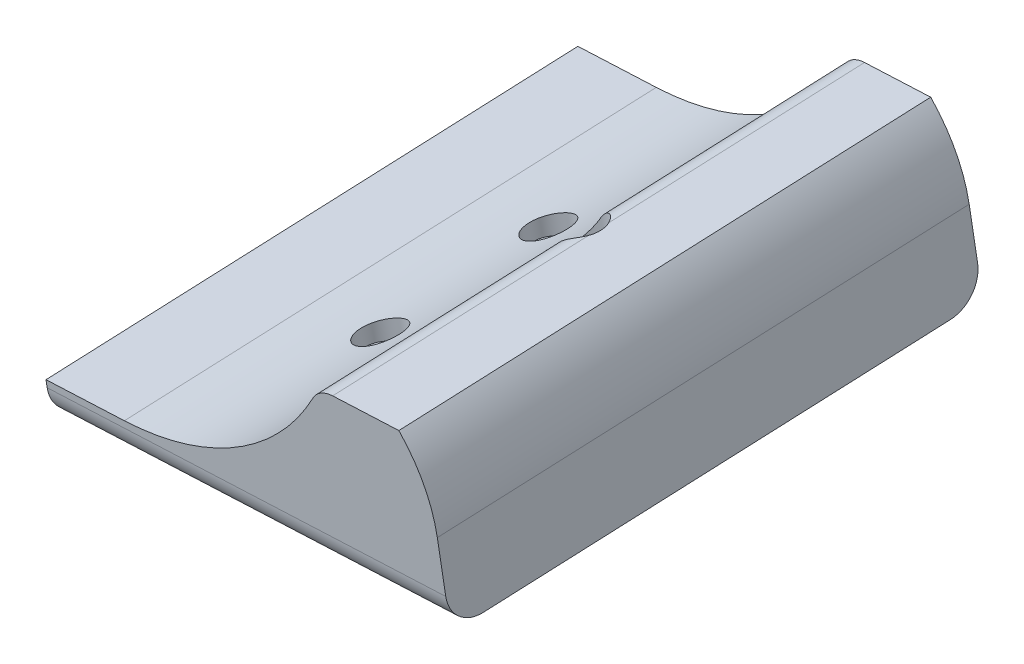
SolidWorks part; units mm, degrees
material "ABS"
ref_plane "Front Plane" through (0, 0, 0) normal (0, 0, 1) x (1, 0, 0)
ref_plane "Top Plane" through (0, 0, 0) normal (0, 1, 0) x (1, 0, 0)
ref_plane "Right Plane" through (0, 0, 0) normal (1, 0, 0) x (0, 0, -1)
other "Configuration Table"
sketch "草图1" plane through (-39.5961, -89.3101, 1121.4165) normal (0.0352, 0.0793, -0.9962) x (-0.9994, 0.0028, -0.0351)
  line L0 (-262.0756, 359.156) -> (-261.6287, 364.136) construction
  line L1 (-262.0756, 359.156) -> (-321.8355, 364.5185) construction
  line L2 (-321.3886, 369.4985) -> (-321.8355, 364.5185) construction
  line L3 (-262.0756, 359.156) -> (-261.6287, 364.136)
  line L4 (-262.0756, 359.156) -> (-321.8355, 364.5185)
  line L5 (-320.7344, 376.7892) -> (-321.3886, 369.4985)
  line L6 (-321.3886, 369.4985) -> (-261.6287, 364.136)
  line L7 (-261.6287, 364.136) -> (-261.4359, 366.2849)
  line L8 (-260.4634, 369.7758) -> (-248.7767, 393.7308)
  line L9 (-287.343, 419.7795) -> (-315.6618, 388.4015)
  line L10 (-320.7344, 376.7892) -> (-321.3886, 369.4985)
  line L12 (-261.6287, 364.136) -> (-261.4359, 366.2849)
  line L13 (-260.4634, 369.7758) -> (-248.7767, 393.7308)
  line L14 (-287.343, 419.7795) -> (-315.6618, 388.4015)
  line L15 (-321.3886, 369.4985) -> (-321.8355, 364.5185)
  arc A3 (-260.4634, 369.7758) -> (-261.4359, 366.2849) centre (-251.4759, 365.3912) ccw
  arc A4 (-248.7767, 393.7308) -> (-287.343, 419.7795) centre (-269.8973, 404.0347) ccw
  arc A5 (-315.6618, 388.4015) -> (-320.7344, 376.7892) centre (-300.8144, 375.0017) ccw
  arc A6 (-260.4634, 369.7758) -> (-261.4359, 366.2849) centre (-251.4759, 365.3912) ccw
  arc A7 (-248.7767, 393.7308) -> (-287.343, 419.7795) centre (-269.8973, 404.0347) ccw
  arc A8 (-315.6618, 388.4015) -> (-320.7344, 376.7892) centre (-300.8144, 375.0017) ccw
  dimension "D1" = 0
extrude "凸台-拉伸1" add sketch "草图1" along normal up to surface (75 mm away)
sketch "草图2" plane through (351.4955, 30.4789, 14.8383) normal (0.9954, 0.0863, 0.042) x (0.0419, 0.0036, -0.9991)
  line L0 (-1074.8827, 277.7422) -> (-1077.4503, 311.4279) construction
  line L1 (-1074.8827, 277.7422) -> (-1073.9691, 265.7578) construction
  line L2 (-1073.4128, 258.4589) -> (-1073.9691, 265.7578) construction
  line L3 (-1142.8303, 248.1531) -> (-1078.0183, 253.0934) construction
  line L4 (-1149.6657, 272.0419) -> (-1152.2334, 305.7275) construction
  line L5 (-1148.7522, 260.0574) -> (-1149.6657, 272.0419) construction
  line L6 (-1148.1958, 252.7586) -> (-1148.7522, 260.0574) construction
  line L7 (-1074.8827, 277.7422) -> (-1078.7049, 327.8868) construction
  line L8 (-1074.8827, 277.7422) -> (-1073.9691, 265.7578) construction
  line L9 (-1073.4128, 258.4589) -> (-1073.9691, 265.7578) construction
  line L10 (-1142.8303, 248.1531) -> (-1078.0183, 253.0934) construction
  line L11 (-1149.6657, 272.0419) -> (-1153.488, 322.1865) construction
  line L12 (-1148.7522, 260.0574) -> (-1149.6657, 272.0419) construction
  line L13 (-1148.1958, 252.7586) -> (-1148.7522, 260.0574) construction
  line L14 (-1153.488, 322.1865) -> (-1078.7049, 327.8868) construction
  line L15 (-1054.9405, 279.2623) -> (-1060.2829, 349.3491)
  line L16 (-1174.9502, 340.6086) -> (-1060.2829, 349.3491)
  line L17 (-1169.6079, 270.5218) -> (-1174.9502, 340.6086)
  line L18 (-1168.6943, 258.5373) -> (-1169.6079, 270.5218)
  line L19 (-1168.138, 251.2385) -> (-1168.6943, 258.5373)
  line L20 (-1141.3102, 228.2109) -> (-1076.4982, 233.1512)
  line L21 (-1053.4706, 259.979) -> (-1054.027, 267.2778)
  line L22 (-1054.9405, 279.2623) -> (-1054.027, 267.2778)
  line L23 (-1075.3812, 277.7042) -> (-1079.1655, 327.3503)
  line L24 (-1152.9514, 321.726) -> (-1079.1655, 327.3503)
  line L25 (-1149.1672, 272.0799) -> (-1152.9514, 321.726)
  line L26 (-1148.2536, 260.0954) -> (-1149.1672, 272.0799)
  line L27 (-1147.6973, 252.7966) -> (-1148.2536, 260.0954)
  line L28 (-1142.8683, 248.6516) -> (-1078.0563, 253.5919)
  line L29 (-1073.9113, 258.4209) -> (-1074.4677, 265.7198)
  line L30 (-1075.3812, 277.7042) -> (-1074.4677, 265.7198)
  arc A0 (-1078.0183, 253.0934) -> (-1073.4128, 258.4589) centre (-1078.3983, 258.0789) ccw construction
  arc A1 (-1148.1958, 252.7586) -> (-1142.8303, 248.1531) centre (-1143.2103, 253.1386) ccw construction
  arc A2 (-1078.0183, 253.0934) -> (-1073.4128, 258.4589) centre (-1078.3983, 258.0789) ccw construction
  arc A3 (-1148.1958, 252.7586) -> (-1142.8303, 248.1531) centre (-1143.2103, 253.1386) ccw construction
  arc A4 (-1168.138, 251.2385) -> (-1141.3102, 228.2109) centre (-1143.2103, 253.1386) ccw
  arc A5 (-1076.4982, 233.1512) -> (-1053.4706, 259.979) centre (-1078.3983, 258.0789) ccw
  arc A6 (-1147.6973, 252.7966) -> (-1142.8683, 248.6516) centre (-1143.2103, 253.1386) ccw
  arc A7 (-1078.0563, 253.5919) -> (-1073.9113, 258.4209) centre (-1078.3983, 258.0789) ccw
  dimension "D1" = 20
  dimension "D2" = 0.5
extrude "切除-拉伸2" cut sketch "草图2" against normal blind 89
sketch "草图4" plane through (-39.5785, -89.2704, 1120.9184) normal (-0.0352, -0.0793, 0.9962) x (0.9994, -0.0028, 0.0351)
  line L0 (273.2936, 366.1867) -> (261.5393, 365.132)
  line L1 (261.4359, 366.2849) -> (261.6287, 364.136) construction
  line L2 (262.0309, 359.654) -> (321.7908, 365.0165) construction
  line L3 (232.0494, 400.6384) -> (235.4457, 362.7905)
  line L4 (235.4457, 362.7905) -> (261.5393, 365.132)
  arc A0 (273.2936, 366.1867) -> (232.0494, 400.6384) centre (269.8973, 404.0347) ccw
  dimension "D1" = 76
extrude "切除-拉伸3" cut sketch "草图4" against normal blind 89
sketch "草图7" plane through (-39.5785, -89.2704, 1120.9184) normal (-0.0352, -0.0793, 0.9962) x (0.9994, -0.0028, 0.0351)
  line L0 (303.8665, 387.0025) -> (315.9406, 388.086)
  line L1 (305.2988, 387.131) -> (327.9246, 389.1613) construction
  line L2 (303.8665, 387.0025) -> (302.2619, 404.8841)
  line L3 (302.2619, 404.8841) -> (314.336, 405.9675)
  line L4 (314.336, 405.9675) -> (315.9406, 388.086)
  arc A0 (273.2936, 366.1867) -> (307.3504, 397.6107) centre (269.8973, 404.0347) ccw construction
  arc A1 (320.7344, 376.7892) -> (315.6618, 388.4015) centre (300.8144, 375.0017) ccw construction
extrude "切除-拉伸4" cut sketch "草图7" against normal blind 102
fillet "圆角1" radius 4 1 edges at (265.4014, 298.5976, 1125.4368)
sketch "草图8" plane through (-29.9039, 332.4869, 25.4235) normal (0.0893, -0.9931, -0.0759) x (0.996, 0.0891, 0.0068)
  line L0 (254.5129, 1097.8373) -> (314.4754, 1099.9563) construction
  line L1 (253.3651, 1130.3171) -> (255.6607, 1065.3576) construction
  line L2 (313.3276, 1132.4361) -> (315.6232, 1067.4766) construction
  line L3 (283.3463, 1131.3766) -> (285.6419, 1066.4171) construction
  line L4 (253.3651, 1130.3171) -> (313.3276, 1132.4361) construction
  line L5 (255.6607, 1065.3576) -> (315.6232, 1067.4766) construction
  line L6 (277.3354, 1110.3425) -> (284.4941, 1098.8968) construction
  circle A0 centre (284.4941, 1098.8968) radius 13.5 construction
  circle A1 centre (277.3354, 1110.3425) radius 1.7
  circle A2 centre (297.9857, 1099.3736) radius 1.7
  circle A3 centre (278.1613, 1086.9744) radius 1.7
  dimension "D1" = 27
  dimension "D2" = 3.4
  dimension "D4" = 30
  dimension "D3" = 3
extrude "切除-拉伸5" cut sketch "草图8" against normal blind 27
sketch "草图9" plane through (-32.0029, 355.8248, 27.2081) normal (-0.0893, 0.9931, 0.0759) x (0.996, 0.0891, 0.0068)
  circle A0 centre (278.1613, -1086.9744) radius 3.1
  circle A1 centre (297.9857, -1099.3736) radius 3.1
  circle A2 centre (277.3354, -1110.3425) radius 3.1
  dimension "D1" = 6.2
  dimension "D2" = 6.2
  dimension "D3" = 6.2
extrude "切除-拉伸6" cut sketch "草图9" against normal offset from surface (19.5 mm away) 4 up to face at (248.0162, 272.6836, 1134.4228)
